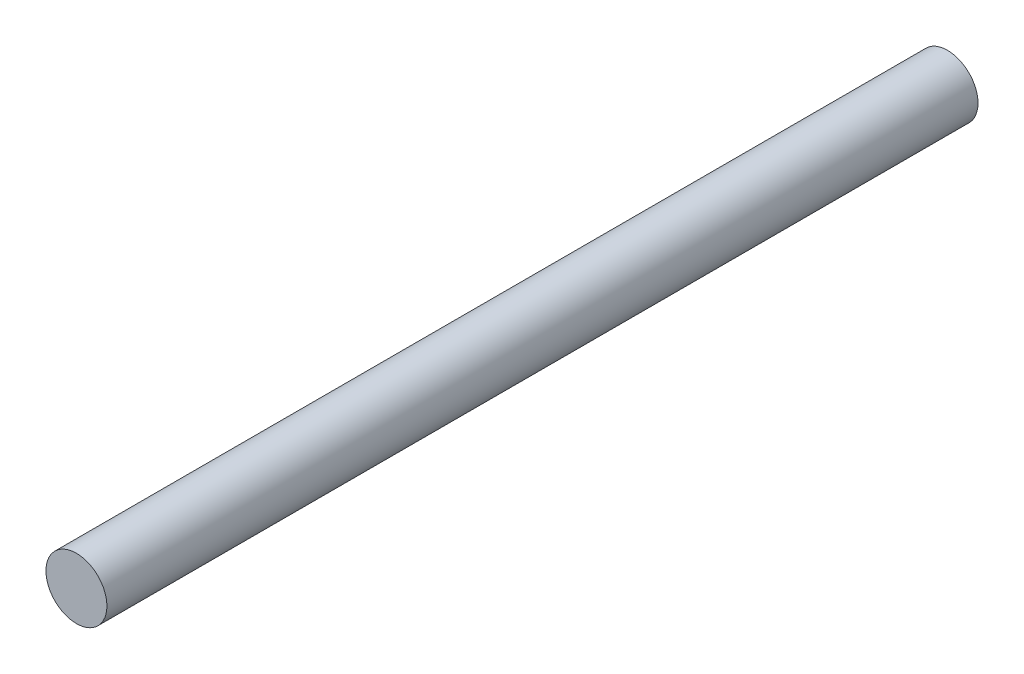
SolidWorks part; units mm, degrees
ref_plane "Plan de face" through (0, 0, 0) normal (0, 0, 1) x (1, 0, 0)
ref_plane "Plan de dessus" through (0, 0, 0) normal (0, 1, 0) x (1, 0, 0)
ref_plane "Plan de droite" through (0, 0, 0) normal (1, 0, 0) x (0, 0, -1)
sketch "Esquisse2" plane through (0, 0, 0) normal (0, 0, 1) x (1, 0, 0)
  circle A0 centre (0, 0) radius 2
  dimension "D1" = 4
extrude "Boss.-Extru.1" add sketch "Esquisse2" along normal mid plane 57.15
